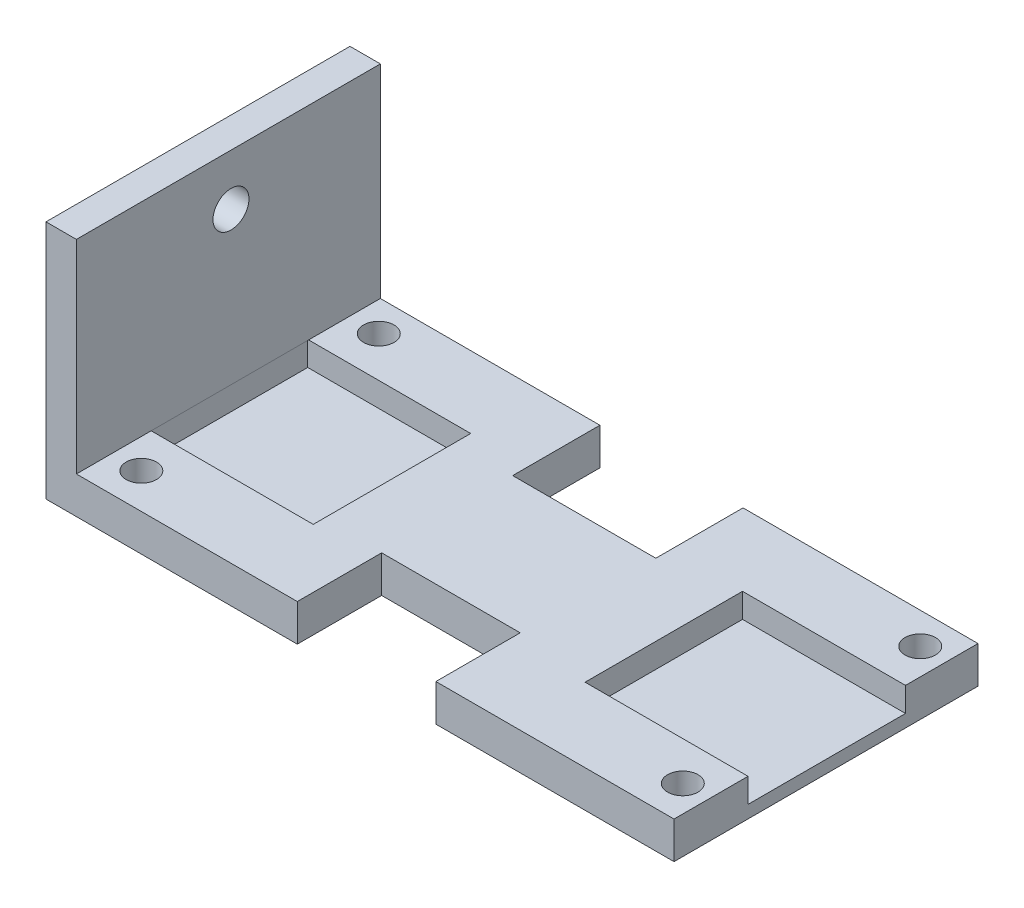
SolidWorks part; units mm, degrees
ref_plane "Front Plane" through (0, 0, 0) normal (0, 0, 1) x (1, 0, 0)
ref_plane "Top Plane" through (0, 0, 0) normal (0, 1, 0) x (1, 0, 0)
ref_plane "Right Plane" through (0, 0, 0) normal (1, 0, 0) x (0, 0, -1)
sketch "Sketch5" plane through (0, 0, 0) normal (1, 0, 0) x (0, 0, -1)
  line L1 (-6.1557, -12.5566) -> (19.2443, -12.5566)
  line L2 (-6.1557, -12.5566) -> (-6.1557, 12.8434)
  line L3 (-6.1557, 12.8434) -> (19.2443, 12.8434)
  line L4 (19.2443, -12.5566) -> (19.2443, 12.8434)
  dimension "D1" = 25.4
  dimension "D2" = 25.4
extrude "Boss-Extrude2" add sketch "Sketch5" against normal blind 2.54
sketch "Sketch6" plane through (0, 0, 0) normal (1, 0, 0) x (0, 0, -1)
  line L1 (-6.1557, -12.5566) -> (19.2443, -12.5566)
  line L2 (-6.1557, -12.5566) -> (-6.1557, -9.4699)
  line L3 (-6.1557, -9.4699) -> (19.2443, -9.4699)
  line L4 (19.2443, -12.5566) -> (19.2443, -9.4699)
extrude "Boss-Extrude3" add sketch "Sketch6" along normal blind 49.9364
sketch "Sketch7" plane through (0, -9.4699, 0) normal (0, 1, 0) x (1, 0, 0)
  circle A0 centre (2.4798, 16.6315) radius 1.27
  circle A1 centre (47.7252, -3.2108) radius 1.27
  circle A2 centre (47.7235, 16.6308) radius 1.27
  circle A3 centre (2.4815, -3.2122) radius 1.27
  dimension "D1" = 2.54
  dimension "D2" = 19.8438
  dimension "D3" = 45.2437
extrude "Cut-Extrude1" cut sketch "Sketch7" against normal blind 49.9364
sketch "Sketch8" plane through (0, 0, 0) normal (1, 0, 0) x (0, 0, -1)
  line L0 (19.2443, -9.4699) -> (-6.1557, -9.4699) construction
  circle A0 centre (6.7608, 3.2301) radius 1.5036
  dimension "D1" = 12.7
extrude "Cut-Extrude2" cut sketch "Sketch8" against normal blind 49.9364
sketch "Sketch9" plane through (0, -9.4699, 0) normal (0, 1, 0) x (1, 0, 0)
  line L9 (18.3433, 19.2443) -> (30.3037, 19.2443)
  line L10 (18.3433, 19.2443) -> (18.3433, 11.9554)
  line L11 (18.3433, 11.9554) -> (30.3037, 11.9554)
  line L12 (30.3037, 19.2443) -> (30.3037, 11.9554)
  line L13 (18.4588, 0.8924) -> (30.0365, 0.8924)
  line L14 (18.4588, 0.8924) -> (18.4588, -6.2232)
  line L15 (18.4588, -6.2232) -> (30.0365, -6.2232)
  line L16 (30.0365, 0.8924) -> (30.0365, -6.2232)
extrude "Cut-Extrude4" cut sketch "Sketch9" against normal blind 5.08
sketch "Sketch10" plane through (0, -9.4699, 0) normal (0, 1, 0) x (1, 0, 0)
  line L0 (13.5423, 13.2482) -> (-0.0748, 13.2482)
  line L1 (49.9364, 13.1853) -> (36.3193, 13.1853)
  line L2 (49.9364, 13.1853) -> (49.9364, 0.0292)
  line L3 (49.9364, 0.0292) -> (36.3193, 0.0292)
  line L4 (36.3193, 13.1853) -> (36.3193, 0.0292)
  line L5 (13.5423, 13.2482) -> (13.5423, 0.0921)
  line L6 (13.5423, 0.0921) -> (-0.0748, 0.0921)
  line L7 (-0.0748, 13.2482) -> (-0.0748, 0.0921)
extrude "Cut-Extrude5" cut sketch "Sketch10" against normal blind 2.032
sketch "Sketch11" plane through (0, -12.5566, 0) normal (0, -1, 0) x (1, 0, 0)
  line L0 (30.0365, 6.1557) -> (30.0365, -0.8924)
  line L1 (30.0365, -0.8924) -> (18.4588, -0.8924)
  line L2 (18.4588, -0.8924) -> (18.4588, 6.1557)
  line L3 (18.4588, 6.1557) -> (12.321, 6.1557)
  line L4 (12.321, 6.1557) -> (12.321, -19.2443)
  line L5 (12.321, -19.2443) -> (18.3433, -19.2443)
  line L6 (18.3433, -19.2443) -> (18.3433, -11.9554)
  line L7 (18.3433, -11.9554) -> (30.3037, -11.9554)
  line L8 (30.3037, -11.9554) -> (30.3037, -19.2443)
  line L9 (30.3037, -19.2443) -> (36.21, -19.2443)
  line L10 (36.21, -19.2443) -> (36.21, 6.1557)
  line L11 (36.21, 6.1557) -> (30.0365, 6.1557)
sketch "Sketch12" plane through (0, 0, 0) normal (1, 0, 0) x (0, 0, -1)
  line L1 (-6.1557, 12.8434) -> (19.2443, 12.8434)
  line L2 (-6.1557, 12.8434) -> (-6.1557, 7.5068)
  line L3 (-6.1557, 7.5068) -> (19.2443, 7.5068)
  line L4 (19.2443, 12.8434) -> (19.2443, 7.5068)
extrude "Cut-Extrude6" cut sketch "Sketch12" against normal blind 2.54
